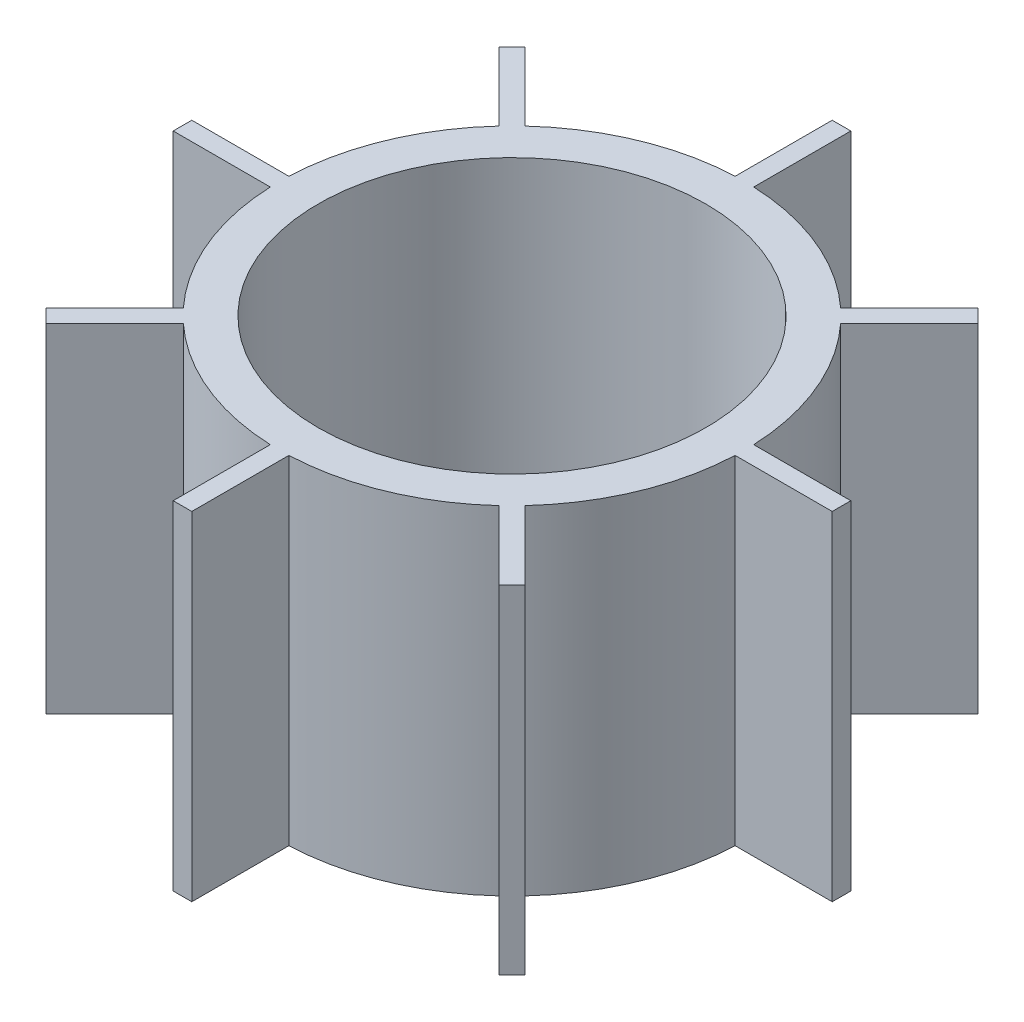
SolidWorks part; units mm, degrees
ref_plane "Front Plane" through (0, 0, 0) normal (0, 0, 1) x (1, 0, 0)
ref_plane "Top Plane" through (0, 0, 0) normal (0, 1, 0) x (1, 0, 0)
ref_plane "Right Plane" through (0, 0, 0) normal (1, 0, 0) x (0, 0, -1)
sketch "Sketch1" plane through (0, 0, 0) normal (0, 1, 0) x (1, 0, 0)
  line L0 (0, 0) -> (0, 31.75) construction
  circle A0 centre (0, 0) radius 38.1
  circle A1 centre (0, 0) radius 31.75
  circle A3 centre (0, 0) radius 31.75 construction
  point P5 (31.75, 0)
  dimension "D1" = 76.2
  dimension "D2" = 6.35
extrude "Boss-Extrude1" add sketch "Sketch1" along normal blind 55.372
ref_plane "Plane1" through (0, 0, 53.975) normal (0, 0, 1) x (1, 0, 0)
sketch "Sketch2" plane through (0, 0, 53.975) normal (0, 0, 1) x (1, 0, 0)
  line L0 (0, 55.372) -> (0, 0) construction
  line L1 (38.1, 55.372) -> (-38.1, 55.372) construction
  line L2 (-38.1, 0) -> (38.1, 0) construction
  line L3 (-1.524, 55.372) -> (1.524, 55.372)
  line L4 (-1.524, 55.372) -> (-1.524, 0)
  line L5 (-1.524, 0) -> (1.524, 0)
  line L6 (1.524, 55.372) -> (1.524, 0)
  line L7 (-1.524, 55.372) -> (1.524, 0) construction
  line L8 (-1.524, 0) -> (1.524, 55.372) construction
  point P5 (0, 27.686)
  dimension "D1" = 3.048
extrude "Boss-Extrude2" add sketch "Sketch2" against normal up to body
pattern_circular "CirPattern1" count 8 over 360 about axis through (0, 0, 0) along (0, 1, 0) of "Boss-Extrude2"
